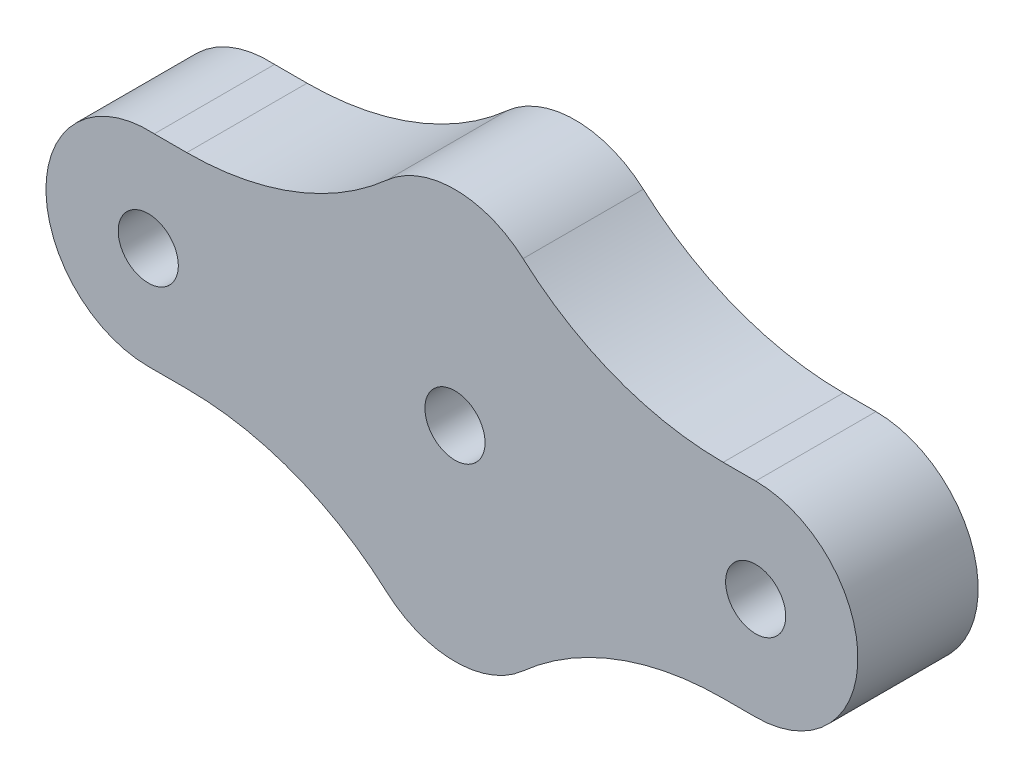
SolidWorks part; units mm, degrees
ref_plane "Front Plane" through (0, 0, 0) normal (0, 0, 1) x (1, 0, 0)
ref_plane "Top Plane" through (0, 0, 0) normal (0, 1, 0) x (1, 0, 0)
ref_plane "Right Plane" through (0, 0, 0) normal (1, 0, 0) x (0, 0, -1)
sketch "Sketch1" plane through (0, 0, 0) normal (0, 0, 1) x (1, 0, 0)
  line L0 (0, 0) -> (3.3, 0)
  line L1 (6.7, 0) -> (10, 0)
  line L2 (10, -3.4) -> (6.7, -3.4)
  line L3 (3.3, -3.4) -> (-0.1, -3.4)
  arc A0 (3.3, 0) -> (6.7, 0) centre (5, 0) cw
  arc A1 (10, 0) -> (10, -3.4) centre (10, -1.7) cw
  arc A2 (6.7, -3.4) -> (3.3, -3.4) centre (5, -3.4) cw
  arc A3 (-0.1, -3.4) -> (0, 0) centre (-0.1, -1.6985) cw
  circle A4 centre (-0.1, -1.6985) radius 0.5
  circle A5 centre (10, -1.7) radius 0.5
  circle A6 centre (5, -1.7) radius 0.5
  point P17 (0, 0)
  dimension "D1" = 3.3
  dimension "D2" = 3.4
  dimension "D3" = 3.3
  dimension "D4" = 3.4
  dimension "D5" = 3.3
  dimension "D6" = 3.4
  dimension "D7" = 3.4
extrude "Boss-Extrude1" add sketch "Sketch1" along normal blind 2
fillet "Fillet1" radius 5 4 edges at (6.7, -3.4, 1) (6.7, 0, 1) (3.3, 0, 1) (3.3, -3.4, 1)
sketch "Sketch2" plane through (0, 0, 0) normal (0, 0, -1) x (-1, 0, 0)
  line L0 (-10, -1.7) -> (-5, -1.7)
